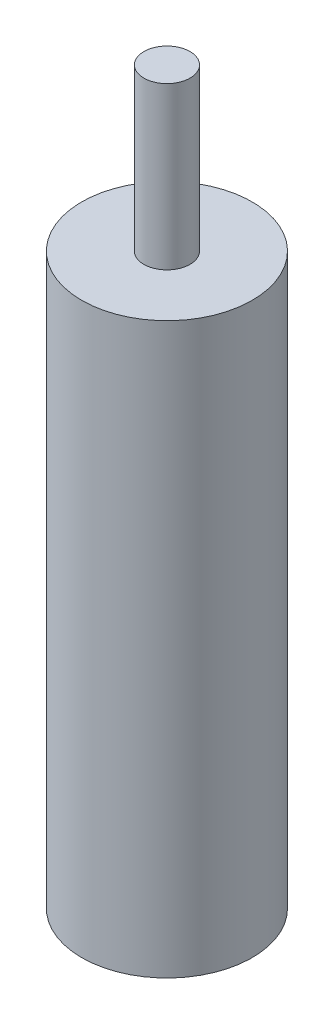
SolidWorks part; units mm, degrees
ref_plane "Front Plane" through (0, 0, 0) normal (0, 0, 1) x (1, 0, 0)
ref_plane "Top Plane" through (0, 0, 0) normal (0, 1, 0) x (1, 0, 0)
ref_plane "Right Plane" through (0, 0, 0) normal (1, 0, 0) x (0, 0, -1)
sketch "Sketch1" plane through (0, 0, 0) normal (0, 1, 0) x (1, 0, 0)
  circle A0 centre (0, 0) radius 18.5
  dimension "D1" = 37
extrude "Boss-Extrude1" add sketch "Sketch1" along normal blind 123.5
sketch "Sketch2" plane through (0, 123.5, 0) normal (0, 1, 0) x (1, 0, 0)
  circle A0 centre (0, 0) radius 5
extrude "Boss-Extrude2" add sketch "Sketch2" along normal blind 35
